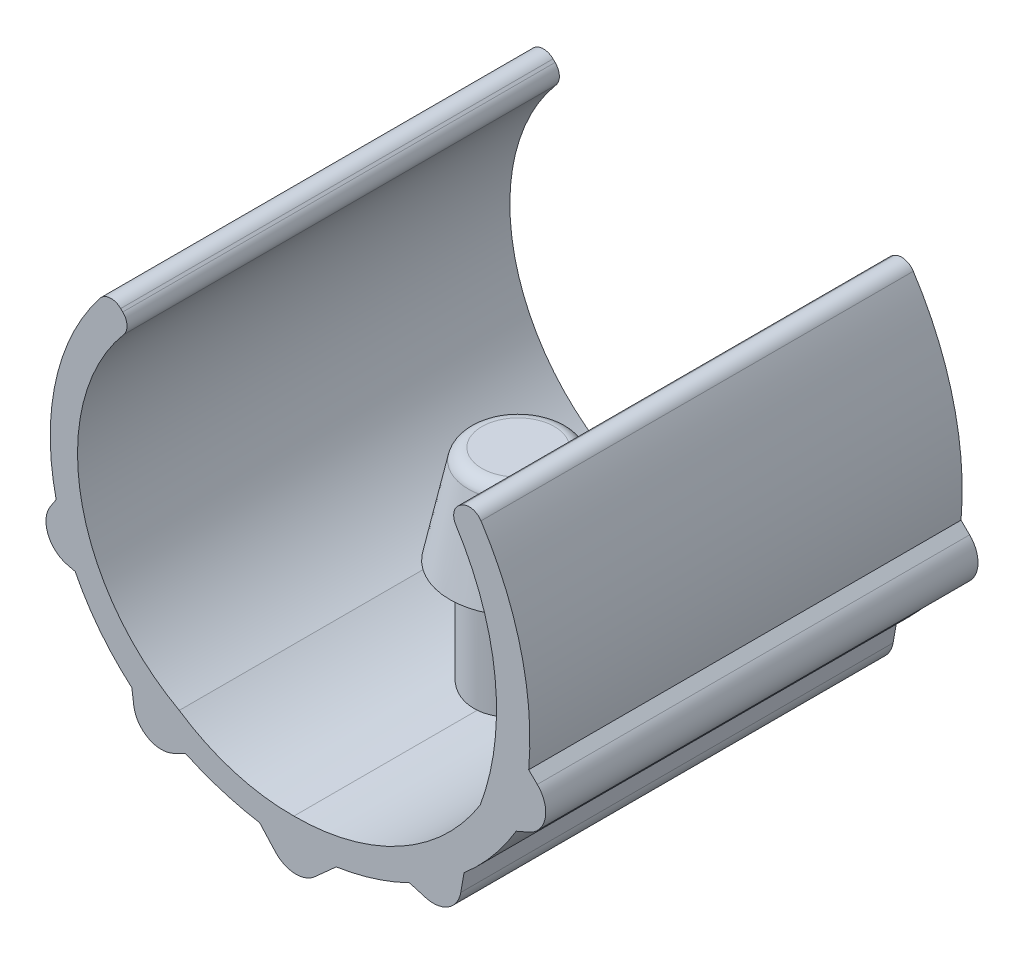
SolidWorks part; units mm, degrees
ref_plane "Front Plane" through (0, 0, 0) normal (0, 0, 1) x (1, 0, 0)
ref_plane "Top Plane" through (0, 0, 0) normal (0, 1, 0) x (1, 0, 0)
ref_plane "Right Plane" through (0, 0, 0) normal (1, 0, 0) x (0, 0, -1)
sketch "Sketch1" plane through (0, 0, 0) normal (0, 0, 1) x (1, 0, 0)
  line L0 (-248.758, 1.0447) -> (261.9086, 1.0447) construction
  line L1 (-163.5782, 204.2914) -> (-186.3767, 226.3411)
  line L2 (156.4218, 206.9705) -> (181.3962, 223.9197)
  line L3 (-240.8705, 15.3939) -> (-268.7856, -26.37)
  line L4 (-268.7856, -26.37) -> (-221.5833, -38.0173)
  line L5 (-164.251, -111.1614) -> (-156.9102, -164.9208)
  line L6 (-156.9102, -164.9208) -> (-109.8369, -141.7643)
  line L7 (-34.694, -164.9208) -> (0, -203.3288)
  line L8 (0, -203.3288) -> (42.8865, -164.9208)
  line L9 (172.3349, -105.3153) -> (163.6266, -155.5211)
  line L10 (163.6266, -155.5211) -> (117.0575, -141.7643)
  line L11 (237.8601, 17.7937) -> (276.7092, -20.0955)
  line L12 (276.7092, -20.0955) -> (225.1621, -42.4505)
  line L13 (0, -352) -> (0, 352) construction
  arc A0 (-163.5782, 204.2914) -> (-116.1457, -107.0776) centre (-21.2832, 66.6706) ccw
  arc A1 (-116.1457, -107.0776) -> (0, -141.7643) centre (-2.5496, 61.4942) ccw
  arc A2 (0, -141.7643) -> (188.7489, -37.6724) centre (1.0383, 79.5272) ccw
  arc A3 (188.7489, -37.6724) -> (156.4218, 206.9705) centre (-58.2978, 54.1402) ccw
  arc A4 (-186.3767, 226.3411) -> (-240.8705, 15.3939) centre (-10.4995, 68.3946) ccw
  arc A5 (-109.8369, -141.7643) -> (-34.694, -164.9208) centre (12.2742, 120.9887) ccw
  arc A6 (42.8865, -164.9208) -> (117.0575, -141.7643) centre (4.0963, 89.6894) ccw
  arc A7 (237.8601, 17.7937) -> (181.3962, 223.9197) centre (-68.3124, 44.7206) ccw
  arc A8 (172.3349, -105.3153) -> (225.1621, -42.4505) centre (4.0963, 89.6894) ccw
  arc A9 (-221.5833, -38.0173) -> (-164.251, -111.1614) centre (-10.4995, 68.3946) ccw
  point P22 (0, -141.7643)
  point P30 (-109.8369, -111.1614)
  dimension "D1" = 320
extrude "Boss-Extrude2" add sketch "Sketch1" along normal blind 438
scale "Scale2" bodies to scale 103 scale about centroid uniform scaling yes scale factor 0.0354
fillet "Fillet1" radius 1 5 edges at (16.7608, -18.898, 219) (12.7577, -23.692, 219) (6.9653, -25.3844, 219) (1.4107, -24.0248, 219) (-2.5497, -19.1201, 219)
fillet "Fillet3" radius 0.5 4 edges at (1.1746, -10.9547, 219) (0.3675, -10.1741, 219) (12.5026, -10.8598, 219) (13.3867, -10.2598, 219)
ref_plane "Plane1" through (0, 0, 226.7526) normal (0, 0, 1) x (1, 0, 0)
ref_plane "Plane2" through (0, 0, 218.5826) normal (0, 0, 1) x (1, 0, 0)
sketch "Sketch2" plane through (0, 0, 218.5826) normal (0, 0, 1) x (1, 0, 0)
  line L0 (0.979, -10.9531) -> (12.6971, -10.9531) construction
  line L1 (6.838, -10.9531) -> (6.838, -23.2034) construction
  line L2 (6.838, -23.2034) -> (-6.7505, -47.1956)
  line L3 (-9.9505, -47.1956) -> (6.838, -23.2034)
  arc A0 (0.8613, -11.301) -> (0.8272, -10.6187) centre (0.4796, -10.9781) ccw construction
  arc A1 (12.9147, -10.5802) -> (12.7736, -11.2623) centre (13.1954, -10.9939) ccw construction
  arc A2 (6.9653, -23.2051) -> (13.647, -19.5202) centre (7.002, -15.3713) ccw construction
ref_plane "Plane3" through (0, -23.2051, 0) normal (0, -1, 0) x (-1, 0, 0)
sketch "Sketch4" plane through (0, -23.2051, 0) normal (0, -1, 0) x (-1, 0, 0)
  line L0 (8.3442, -220.6084) -> (8.3442, -217.4084)
  arc A0 (8.3442, -220.6084) -> (8.3442, -217.4084) centre (8.3442, -219.0084) ccw
  dimension "D1" = 1.6
ref_plane "Plane4" through (0, -19.4051, 0) normal (0, -1, 0) x (-1, 0, 0)
sketch "Sketch5" plane through (0, -19.4051, 0) normal (0, -1, 0) x (-1, 0, 0)
  line L0 (-6.838, -220.1826) -> (-6.838, -216.9826)
  arc A1 (-6.838, -220.1826) -> (-6.838, -216.9826) centre (-6.838, -218.5826) cw
  dimension "D1" = 1.6
  dimension "D2" = 3.2
extrude "Boss-Extrude4" add sketch "Sketch5" along direction (0, -1, 0) on the side of the normal up to surface (3.7984 mm away)
sketch "Sketch8" plane through (0, -19.4051, 0) normal (0, -1, 0) x (-1, 0, 0)
  line L0 (-6.838, -216.9826) -> (-6.838, -220.1826)
  arc A0 (-6.838, -220.1826) -> (-6.838, -216.9826) centre (-6.838, -218.5826) ccw
  arc A1 (-6.838, -216.9826) -> (-6.838, -220.1826) centre (-6.838, -218.5826) ccw construction
  dimension "D1" = 1.6
  dimension "D2" = 3.2
extrude "Boss-Extrude5" add sketch "Sketch8" along direction (0, -1, 0) on the side of the normal up to surface (3.8005 mm away)
sketch "Sketch9" plane through (0, -19.4051, 0) normal (0, 1, 0) x (1, 0, 0)
  circle A0 centre (6.838, -218.5826) radius 2.45
  dimension "D1" = 4.9
extrude "Boss-Extrude6" add sketch "Sketch9" along normal blind 3.5 draft 12
fillet "Fillet4" radius 0.5 1 edges at (6.838, -15.9051, 220.2887)
